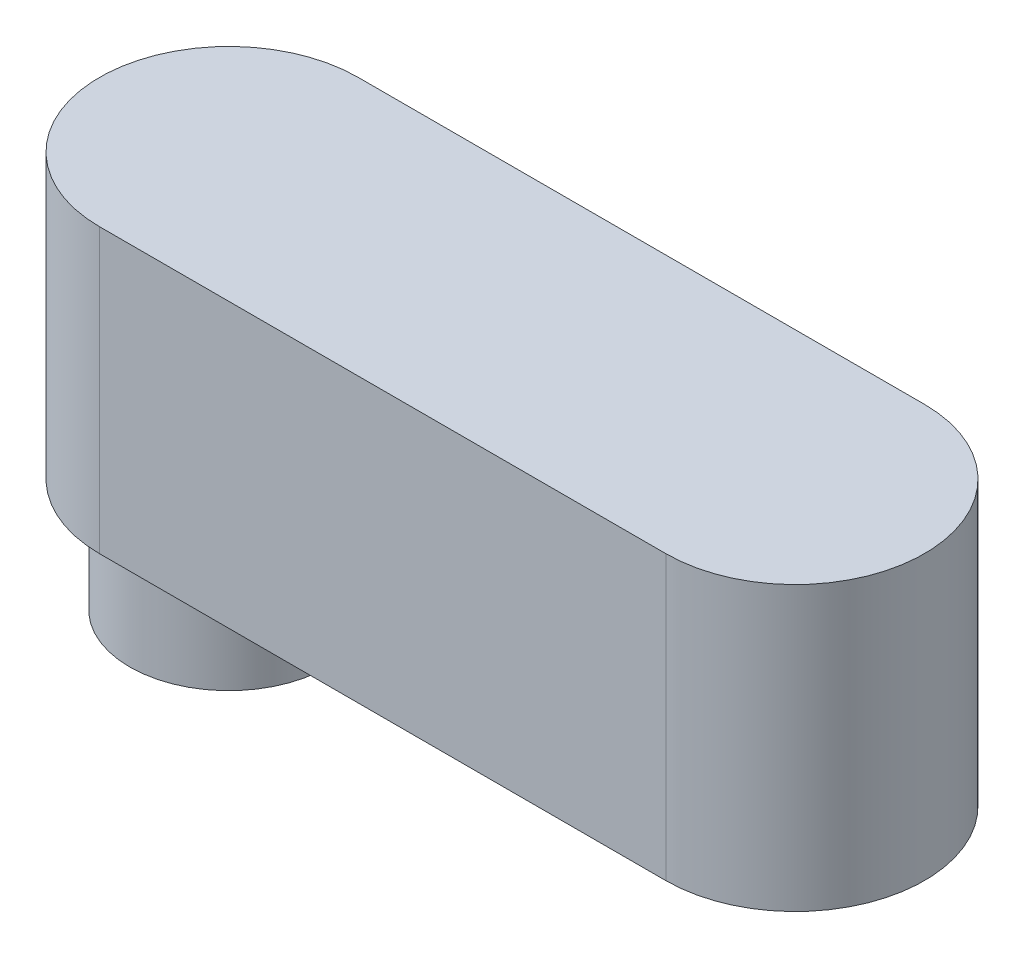
SolidWorks part; units mm, degrees
ref_plane "Plano frontal" through (0, 0, 0) normal (0, 0, 1) x (1, 0, 0)
ref_plane "Plano superior" through (0, 0, 0) normal (0, 1, 0) x (1, 0, 0)
ref_plane "Plano direito" through (0, 0, 0) normal (1, 0, 0) x (0, 0, -1)
sketch "Esboço1" plane through (0, 0, 0) normal (0, 1, 0) x (1, 0, 0)
  line L0 (0, 0) -> (20, 0)
  line L1 (0, -9.1333) -> (20, -9.1333)
  arc A0 (20, 0) -> (20, -9.1333) centre (20, -4.5667) cw
  arc A1 (0, 0) -> (0, -9.1333) centre (0, -4.5667) ccw
  dimension "D2" = 4.5667
  dimension "D1" = 20
extrude "Ressalto-extrusão1" add sketch "Esboço1" along normal blind 10
sketch "Esboço2" plane through (0, 0, 0) normal (0, 1, 0) x (1, 0, 0)
  circle A0 centre (0, -4.5667) radius 3.5
  arc A1 (0, 0) -> (0, -9.1333) centre (0, -4.5667) ccw construction
  dimension "D1" = 7
extrude "Ressalto-extrusão2" add sketch "Esboço2" against normal blind 4
